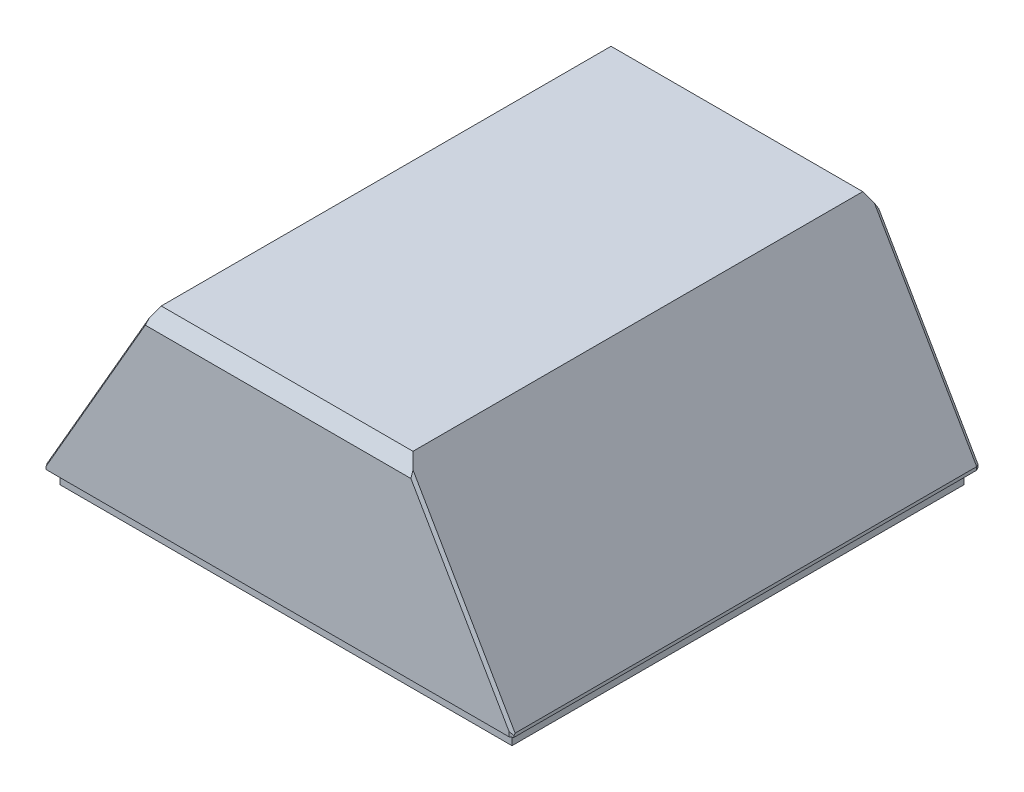
SolidWorks part; units mm, degrees
ref_plane "Front Plane" through (0, 0, 0) normal (0, 0, 1) x (1, 0, 0)
ref_plane "Top Plane" through (0, 0, 0) normal (0, 1, 0) x (1, 0, 0)
ref_plane "Right Plane" through (0, 0, 0) normal (1, 0, 0) x (0, 0, -1)
sketch "Sketch1" plane through (0, 0, 0) normal (0, 1, 0) x (1, 0, 0)
  line L1 (-75, -75) -> (75, -75)
  line L2 (-75, -75) -> (-75, 75)
  line L3 (-75, 75) -> (75, 75)
  line L4 (75, -75) -> (75, 75)
  line L5 (0, 75) -> (0, -75) construction
  line L6 (-75, 0) -> (75, 0) construction
  point P0 (0, 0)
  dimension "D1" = 150
extrude "Boss-Extrude1" add sketch "Sketch1" along normal blind 1
sketch "Sketch2" plane through (0, 1, 0) normal (0, 1, 0) x (1, 0, 0)
  line L1 (-75, -75) -> (75, -75)
  line L2 (-75, -75) -> (-75, 75)
  line L3 (-75, 75) -> (75, 75)
  line L4 (75, -75) -> (75, 75)
  line L5 (0, 75) -> (0, -75) construction
  line L6 (-75, 0) -> (75, 0) construction
  point P0 (0, 0)
extrude "Boss-Extrude2" add sketch "Sketch2" along normal blind 60
chamfer "Chamfer1" distance 60 angle 30 2 edges at (75, 61, 0) (-75, 61, 0)
chamfer "Chamfer2" distance 5 angle 30 2 edges at (0, 61, -75) (0, 61, 75)
chamfer "Chamfer3" distance 1 angle 30 4 edges at (-75, 0.5, 75) (-75, 0.5, -75) (75, 0.5, -75) (75, 0.5, 75)
chamfer "Chamfer4" distance 1 angle 30 4 edges at (-58.6229, 29.366, -75) (58.8342, 29, -75) (58.6229, 29.366, 75) (-58.8342, 29, 75)
sketch "Sketch3" plane through (0, 0, 0) normal (0, -1, 0) x (-1, 0, 0)
  line L1 (72.5, 72.5) -> (-72.5, 72.5)
  line L2 (72.5, 72.5) -> (72.5, -72.5)
  line L3 (72.5, -72.5) -> (-72.5, -72.5)
  line L4 (-72.5, 72.5) -> (-72.5, -72.5)
  line L5 (0, -72.5) -> (0, 72.5) construction
  line L6 (72.5, 0) -> (-72.5, 0) construction
  point P0 (0, 0)
  dimension "D1" = 145
extrude "Boss-Extrude3" add sketch "Sketch3" along normal blind 4.5
